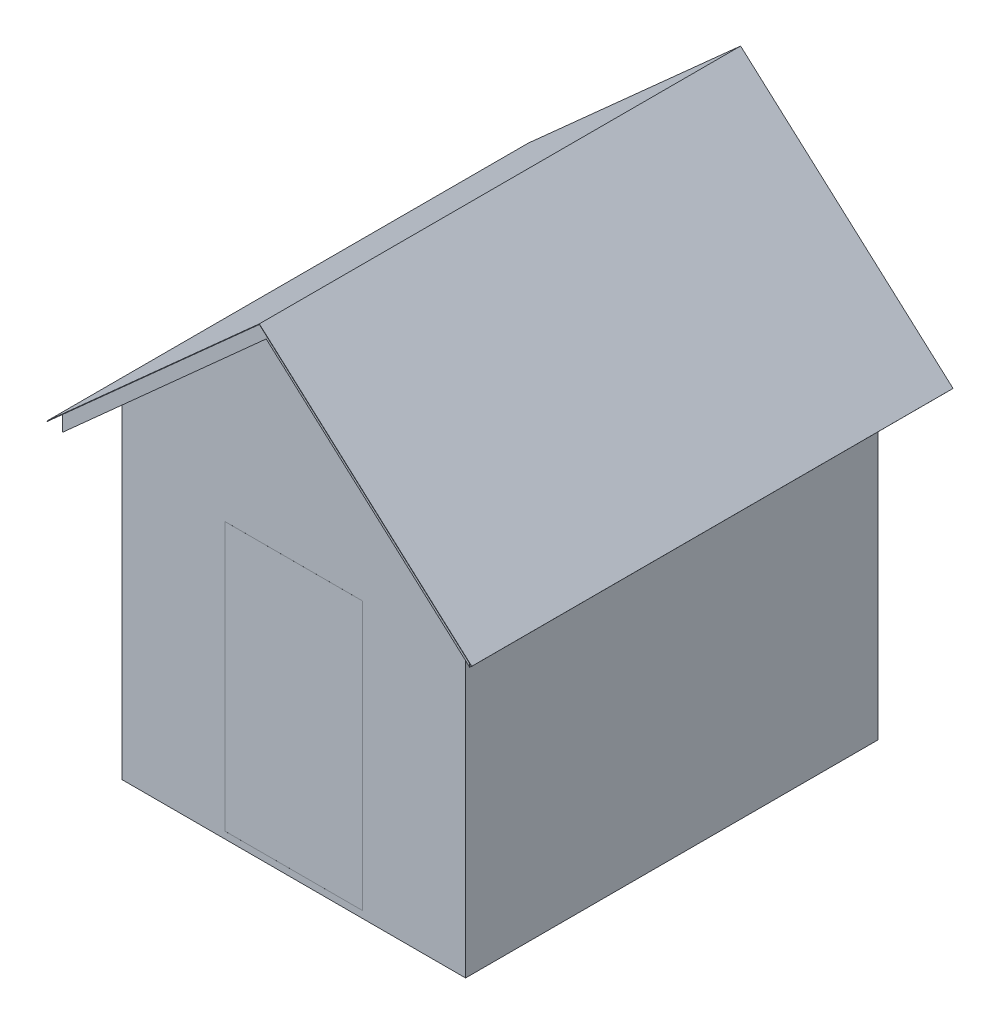
SolidWorks part; units mm, degrees
ref_plane "Front Plane" through (0, 0, 0) normal (0, 0, 1) x (1, 0, 0)
ref_plane "Top Plane" through (0, 0, 0) normal (0, 1, 0) x (1, 0, 0)
ref_plane "Right Plane" through (0, 0, 0) normal (1, 0, 0) x (0, 0, -1)
sketch "Sketch1" plane through (0, 0, 0) normal (0, 1, 0) x (1, 0, 0)
  line L1 (-1250, -1500) -> (1250, -1500)
  line L2 (-1250, -1500) -> (-1250, 1500)
  line L3 (-1250, 1500) -> (1250, 1500)
  line L4 (1250, -1500) -> (1250, 1500)
  line L5 (-1250, -1500) -> (1250, 1500) construction
  line L6 (-1250, 1500) -> (1250, -1500) construction
  point P0 (0, 0)
  dimension "D1" = 2500
  dimension "D2" = 3000
extrude "Boss-Extrude1" add sketch "Sketch1" along normal blind 3500
sketch "Sketch2" plane through (0, 0, 1500) normal (0, 0, 1) x (1, 0, 0)
  line L0 (0, 3500) -> (-1250, 2378.6096)
  line L1 (-1250, 3500) -> (1250, 3500) construction
  line L2 (-1250, 3500) -> (-1250, 0) construction
  line L3 (-1250, 2378.6096) -> (-1250, 3819.8725)
  line L4 (1250, 2378.6096) -> (0, 3500)
  line L5 (1250, 3500) -> (1250, 0) construction
  line L6 (-1250, 3819.8725) -> (1250, 3819.8725)
  line L7 (1250, 3819.8725) -> (1250, 2378.6096)
extrude "Cut-Extrude1" cut sketch "Sketch2" against normal blind 3500
sketch "Sketch3" plane through (0, 0, 1500) normal (0, 0, 1) x (1, 0, 0)
  line L0 (-500, 50) -> (-500, 2000)
  line L1 (-1250, 0) -> (1250, 0) construction
  line L2 (-500, 2000) -> (500, 2000)
  line L3 (500, 2000) -> (500, 50)
  line L5 (-500, 50) -> (500, 50)
  point P6 (0, 2000)
  dimension "D1" = 1000
  dimension "D2" = 2000
shell "Shell1" thickness 100
extrude "Cut-Extrude3" cut sketch "Sketch3" against normal blind 496 contours L2 L3 L5 L0
sketch "Sketch4" plane through (0, 0, 1500) normal (0, 0, 1) x (1, 0, 0)
  line L1 (-499.8742, 1999.8812) -> (499.8761, 1999.8812)
  line L2 (-499.8742, 1999.8812) -> (-499.8742, 50.0503)
  line L3 (-499.8742, 50.0503) -> (499.8761, 50.0503)
  line L4 (499.8761, 1999.8812) -> (499.8761, 50.0503)
extrude "Boss-Extrude2" add sketch "Sketch4" against normal up to surface (100 mm away) separate body up to face at (0, 1426.2935, 1400)
sketch "Sketch5" plane through (0, 0, -1500) normal (0, 0, -1) x (-1, 0, 0)
  line L0 (0, 3500) -> (-1480.2313, 2172.0663)
  line L1 (-1480.2313, 2172.0663) -> (-1480.2313, 2292.0486)
  line L2 (-1480.2313, 2292.0486) -> (0, 3619.9823)
  line L3 (0, 3619.9823) -> (0, 3500) construction
  line L4 (0, 3500) -> (-1250, 2378.6096) construction
  line L5 (1480.2313, 2292.0486) -> (0, 3619.9823)
  line L6 (1480.2313, 2172.0663) -> (1480.2313, 2292.0486)
  line L7 (0, 3500) -> (1480.2313, 2172.0663)
extrude "Boss-Extrude3" add sketch "Sketch5" along normal blind 200 and the other way blind 3200 separate body
sketch "Sketch6" plane through (0, 0, 1700) normal (0, 0, 1) x (1, 0, 0)
  line L0 (-1544.5405, 2235.9168) -> (0, 3619.9823)
  line L1 (0, 3619.9823) -> (1545.1926, 2235.9168)
extrude "Extrude-Thin1" add sketch "Sketch6" along normal blind 50 and the other way blind 3450 separate body thin
